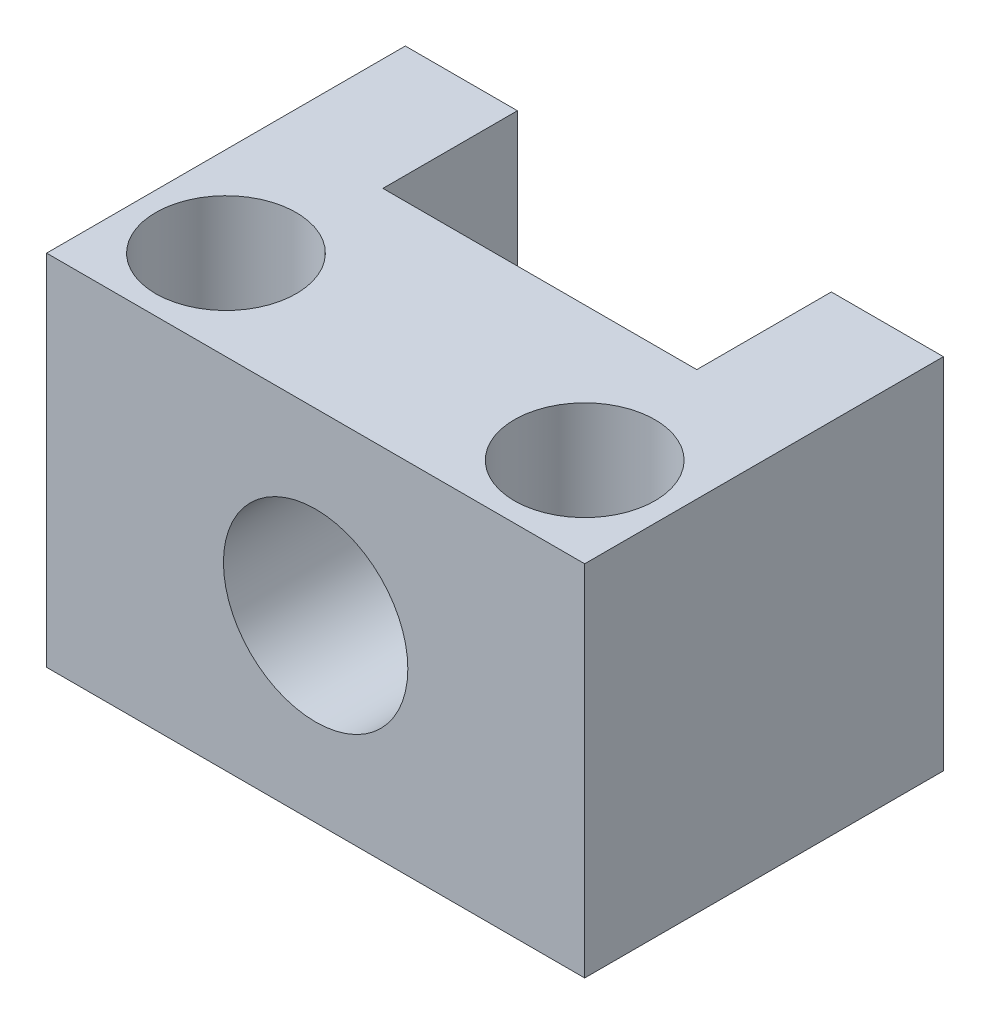
SolidWorks part; units mm, degrees
material "6061-T6 (SS)"
ref_plane "Front Plane" through (0, 0, 0) normal (0, 0, 1) x (1, 0, 0)
ref_plane "Top Plane" through (0, 0, 0) normal (0, 1, 0) x (1, 0, 0)
ref_plane "Right Plane" through (0, 0, 0) normal (1, 0, 0) x (0, 0, -1)
sketch "Sketch1" plane through (0, 0, 0) normal (0, 1, 0) x (1, 0, 0)
  line L1 (0, 0) -> (19.05, 0)
  line L2 (0, 0) -> (0, 12.7)
  line L3 (0, 12.7) -> (19.05, 12.7)
  line L4 (19.05, 0) -> (19.05, 12.7)
  line L5 (0, 0) -> (19.05, 12.7) construction
  line L6 (0, 12.7) -> (19.05, 0) construction
  point P4 (9.525, 6.35)
  dimension "D1" = 12.7
  dimension "D2" = 19.05
extrude "Boss-Extrude1" add sketch "Sketch1" along normal blind 12.7
sketch "Sketch2" plane through (0, 12.7, 0) normal (0, 1, 0) x (1, 0, 0)
  line L0 (9.525, 12.7) -> (9.525, 7.9375) construction
  line L2 (19.05, 12.7) -> (0, 12.7) construction
  line L3 (9.525, 12.7) -> (9.525, 3.175) construction
  line L4 (3.9688, 7.9375) -> (15.0813, 7.9375)
  line L5 (3.9688, 7.9375) -> (3.9688, 12.7)
  line L6 (3.9688, 12.7) -> (15.0813, 12.7)
  line L7 (15.0813, 7.9375) -> (15.0813, 12.7)
  line L8 (3.9688, 7.9375) -> (15.0813, 12.7) construction
  line L9 (3.9688, 12.7) -> (15.0813, 7.9375) construction
  line L10 (19.05, 3.175) -> (0, 3.175) construction
  line L11 (0, 12.7) -> (0, 0) construction
  line L12 (0, 3.175) -> (3.175, 3.175) construction
  line L13 (19.05, 3.175) -> (15.875, 3.175) construction
  circle A0 centre (3.175, 3.175) radius 2.4892
  circle A1 centre (15.875, 3.175) radius 2.4892
  point P4 (9.525, 10.3188)
  point P7 (9.525, 7.9375)
  point P16 (9.525, 3.175)
  dimension "D6" = 4.9784
  dimension "D7" = 4.9784
  dimension "D1" = 4.7625
  dimension "D2" = 11.1125
  dimension "D3" = 9.525
  dimension "D4" = 3.175
  dimension "D5" = 3.175
extrude "Cut-Extrude1" cut sketch "Sketch2" against normal blind 12.7
sketch "Sketch3" plane through (0, 0, 0) normal (0, 0, 1) x (1, 0, 0)
  line L0 (0, 12.7) -> (19.05, 0) construction
  line L1 (0, 0) -> (19.05, 12.7) construction
  circle A0 centre (9.525, 6.35) radius 3.2639
  dimension "D1" = 6.5278
extrude "Cut-Extrude2" cut sketch "Sketch3" against normal blind 12.7
